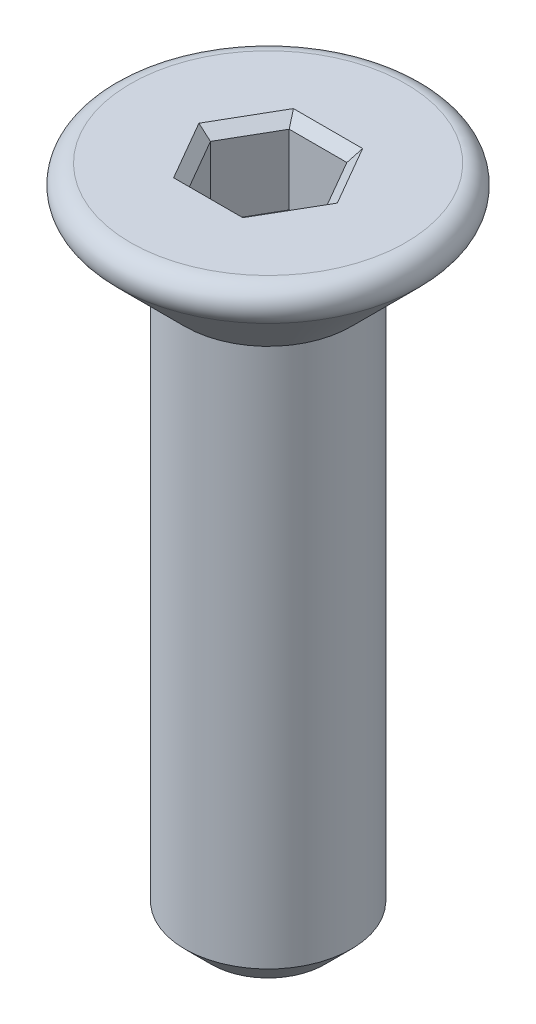
SolidWorks part; units mm, degrees
material "AISI Acier inoxydable type 316L"
ref_plane "Plan de face" through (0, 0, 0) normal (0, 0, 1) x (1, 0, 0)
ref_plane "Plan de dessus" through (0, 0, 0) normal (0, 1, 0) x (1, 0, 0)
ref_plane "Plan de droite" through (0, 0, 0) normal (1, 0, 0) x (0, 0, -1)
sketch "Esquisse1" plane through (0, 0, 0) normal (0, 0, 1) x (1, 0, 0)
  line L0 (0, 6.973) -> (0, -16.342) construction
  line L1 (1.25, -9.6) -> (0.85, -10)
  line L2 (0, 0) -> (2.0672, 0)
  line L4 (2.2672, -0.4828) -> (1.25, -1.5)
  line L5 (1.25, -1.5) -> (1.25, -9.6)
  line L7 (0.85, -10) -> (0, -10)
  line L8 (0, -10) -> (0, 0)
  arc A0 (2.0672, 0) -> (2.2672, -0.4828) centre (2.0672, -0.2828) cw
  point P9 (1.25, -10)
  dimension "D5" = 45
  dimension "D1" = 1.5
  dimension "D2" = 4.7
  dimension "D3" = 2.5
  dimension "D4" = 10
revolve "Révolution1" add sketch "Esquisse1" angle 360 about L0
cosmetic thread "Représentation de filetage1" parameters "D2"=2.439
sketch "Esquisse2" plane through (0, 0, 0) normal (0, 1, 0) x (1, 0, 0)
  line L0 (-0.866, 0) -> (-0.433, -0.75)
  line L1 (0.866, 0) -> (0.433, 0.75)
  line L2 (0.433, 0.75) -> (-0.433, 0.75)
  line L3 (-0.433, 0.75) -> (-0.866, 0)
  line L4 (-0.433, -0.75) -> (0.433, -0.75)
  line L5 (0.433, -0.75) -> (0.866, 0)
  circle A0 centre (0, 0) radius 0.75 construction
  dimension "D1" = 1.5
extrude "Enlèv. mat.-Extru.1" cut sketch "Esquisse2" against normal blind 1.2
chamfer "Chanfrein1" distance 0.15 angle 45 6 edges at (-0.6495, 0, -0.375) (-0.6495, 0, 0.375) (0, 0, 0.75) (0.6495, 0, 0.375) (0.6495, 0, -0.375) (0, 0, -0.75)
